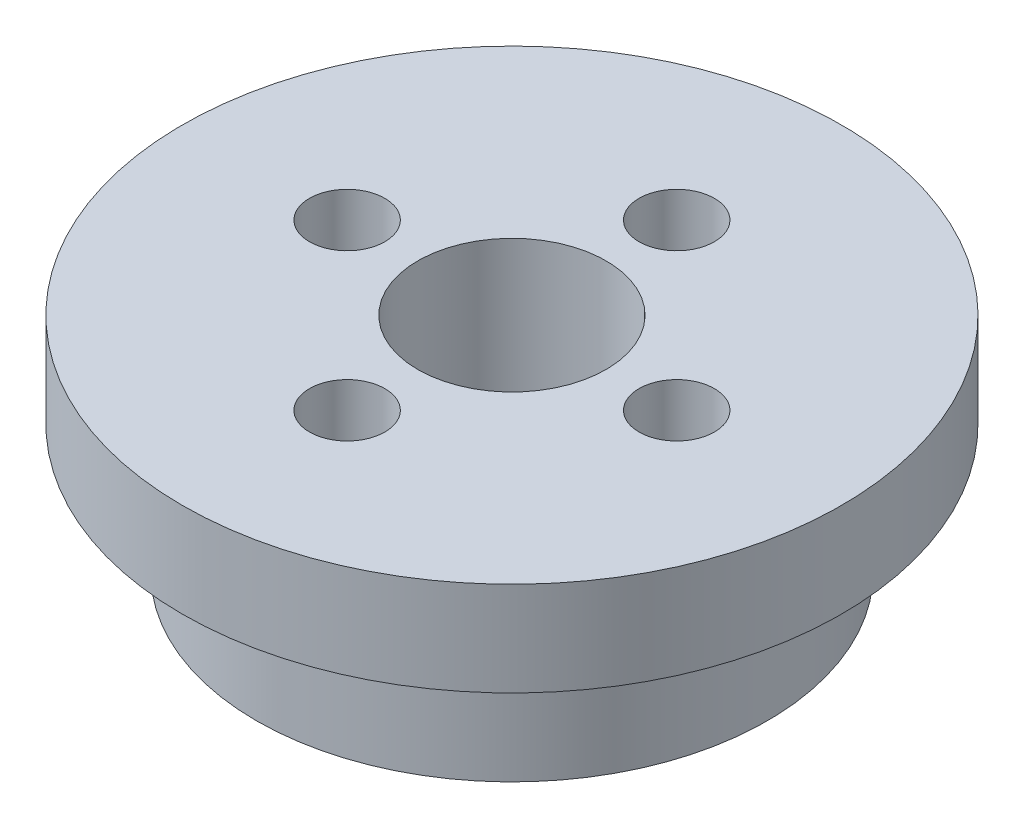
SolidWorks part; units mm, degrees
ref_plane "前视基准面" through (0, 0, 0) normal (0, 0, 1) x (1, 0, 0)
ref_plane "上视基准面" through (0, 0, 0) normal (0, 1, 0) x (1, 0, 0)
ref_plane "右视基准面" through (0, 0, 0) normal (1, 0, 0) x (0, 0, -1)
sketch "草图3" plane through (0, 0, 0) normal (0, 1, 0) x (1, 0, 0)
  circle A0 centre (0, 0) radius 10.85
  dimension "D1" = 21.7
extrude "凸台-拉伸1" add sketch "草图3" along normal blind 5.5
sketch "草图4" plane through (0, 5.5, 0) normal (0, 1, 0) x (1, 0, 0)
  circle A0 centre (0, 0) radius 14
  dimension "D1" = 28
extrude "凸台-拉伸2" add sketch "草图4" along normal blind 4
sketch "草图5" plane through (0, 9.5, 0) normal (0, 1, 0) x (1, 0, 0)
  line L0 (0, -14) -> (0, 14) construction
  line L1 (-4.65, 1.3568) -> (-7, 2.7135) construction
  line L2 (-1.3568, -4.65) -> (-2.7135, -7) construction
  line L3 (-2.7135, -7) -> (-1.3568, -9.35) construction
  line L4 (-1.3568, -9.35) -> (1.3568, -9.35) construction
  line L5 (1.3568, -9.35) -> (2.7135, -7) construction
  line L6 (2.7135, -7) -> (1.3568, -4.65) construction
  line L7 (1.3568, -4.65) -> (-1.3568, -4.65) construction
  line L8 (-7, 2.7135) -> (-9.35, 1.3568) construction
  line L9 (-9.35, 1.3568) -> (-9.35, -1.3568) construction
  line L10 (-9.35, -1.3568) -> (-7, -2.7135) construction
  line L11 (-7, -2.7135) -> (-4.65, -1.3568) construction
  line L12 (-4.65, -1.3568) -> (-4.65, 1.3568) construction
  line L13 (-14, 0) -> (14, 0) construction
  line L14 (1.3568, 4.65) -> (2.7135, 7) construction
  line L15 (2.7135, 7) -> (1.3568, 9.35) construction
  line L16 (1.3568, 9.35) -> (-1.3568, 9.35) construction
  line L17 (-1.3568, 9.35) -> (-2.7135, 7) construction
  line L18 (-2.7135, 7) -> (-1.3568, 4.65) construction
  line L19 (-1.3568, 4.65) -> (1.3568, 4.65) construction
  line L20 (0, 14) -> (0, -14) construction
  line L21 (4.65, -1.3568) -> (7, -2.7135) construction
  line L22 (7, -2.7135) -> (9.35, -1.3568) construction
  line L23 (9.35, -1.3568) -> (9.35, 1.3568) construction
  line L24 (9.35, 1.3568) -> (7, 2.7135) construction
  line L25 (7, 2.7135) -> (4.65, 1.3568) construction
  line L26 (4.65, 1.3568) -> (4.65, -1.3568) construction
  line L27 (14, 0) -> (-14, 0) construction
  circle A0 centre (0, 0) radius 4
  circle A1 centre (-7, 0) radius 2.35 construction
  circle A2 centre (0, 0) radius 14 construction
  circle A3 centre (0, -7) radius 2.35 construction
  circle A4 centre (0, 7) radius 2.35 construction
  circle A6 centre (7, 0) radius 2.35 construction
  circle A7 centre (0, 7) radius 1.6
  circle A8 centre (7, 0) radius 1.6
  circle A9 centre (0, -7) radius 1.6
  circle A10 centre (-7, 0) radius 1.6
  point P37 (0.1299, -0.075)
  point P43 (0, 0)
  point P45 (0, 0)
  point P51 (0, 0)
  point P56 (0, 0)
  dimension "D1" = 4
  dimension "D3" = 8
  dimension "D2" = 4.7
  dimension "D4" = 3.2
  dimension "D5" = 4
extrude "切除-拉伸1" cut sketch "草图5" against normal blind 50
